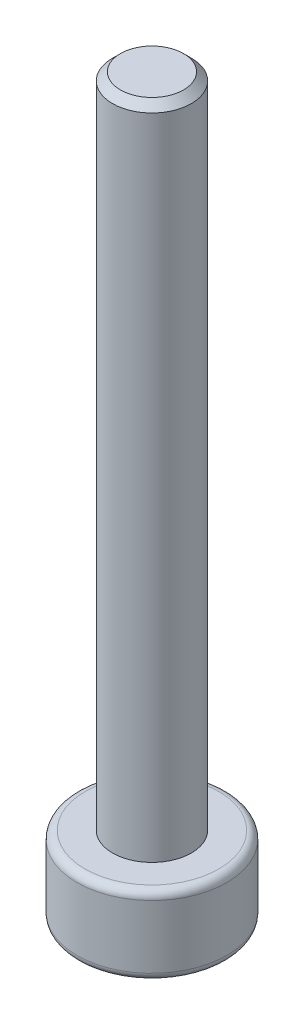
SolidWorks part; units mm, degrees
material "AISI 304"
ref_plane "前视基准面" through (0, 0, 0) normal (0, 0, 1) x (1, 0, 0)
ref_plane "上视基准面" through (0, 0, 0) normal (0, 1, 0) x (1, 0, 0)
ref_plane "右视基准面" through (0, 0, 0) normal (1, 0, 0) x (0, 0, -1)
sketch "草图1" plane through (0, 0, 0) normal (0, 1, 0) x (1, 0, 0)
  circle A0 centre (0, 0) radius 2.85
  dimension "D1" = 5.7
extrude "凸台-拉伸1" add sketch "草图1" along normal blind 3
sketch "草图2" plane through (0, 3, 0) normal (0, 1, 0) x (1, 0, 0)
  circle A0 centre (0, 0) radius 1.5
  dimension "D1" = 3
extrude "凸台-拉伸2" add sketch "草图2" along normal blind 25
sketch "草图3" plane through (0, 0, 0) normal (0, -1, 0) x (1, 0, 0)
  circle A0 centre (0, 0) radius 1.29
  dimension "D1" = 2.58
extrude "切除-拉伸1" cut sketch "草图3" against normal blind 1.3
fillet "圆角1" radius 0.3 2 edges at (0, 3, 2.85) (0, 0, 2.85)
chamfer "倒角1" distance 0.3 angle 45 1 edges at (0, 28, 1.5)
chamfer "倒角2" distance 0.15 angle 45 1 edges at (0, 0, -1.29)
